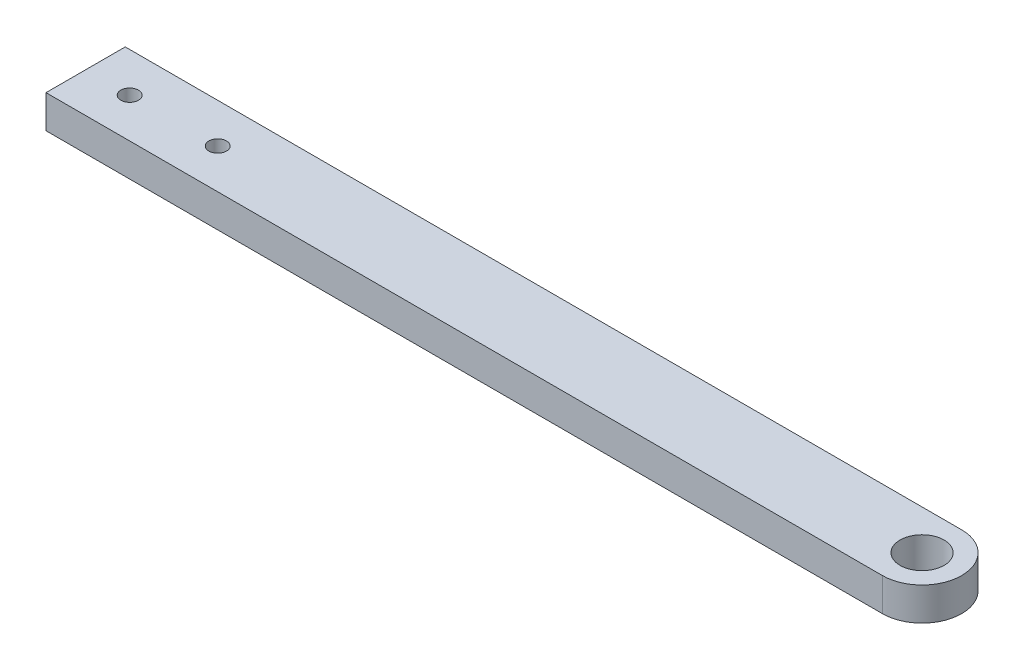
SolidWorks part; units mm, degrees
ref_plane "Front Plane" through (0, 0, 0) normal (0, 0, 1) x (1, 0, 0)
ref_plane "Top Plane" through (0, 0, 0) normal (0, 1, 0) x (1, 0, 0)
ref_plane "Right Plane" through (0, 0, 0) normal (1, 0, 0) x (0, 0, -1)
sketch "Sketch1" plane through (0, 0, 0) normal (0, 1, 0) x (1, 0, 0)
  line L3 (0, 9) -> (-190, 9)
  line L4 (-190, 9) -> (-190, -9)
  line L5 (-190, -9) -> (0, -9)
  arc A1 (0, -9) -> (0, 9) centre (0, 0) ccw
  dimension "D1" = 18
  dimension "D2" = 190
extrude "Boss-Extrude1" add sketch "Sketch1" along normal blind 7.5
sketch "Sketch2" plane through (0, 7.5, 0) normal (0, 1, 0) x (1, 0, 0)
  line L0 (-190, 9) -> (-190, -9) construction
  circle A0 centre (-180, 0) radius 2
  circle A1 centre (-160, 0) radius 2
  dimension "D1" = 4
  dimension "D2" = 20
  dimension "D3" = 10
extrude "Cut-Extrude1" cut sketch "Sketch2" against normal through all
sketch "Sketch3" plane through (0, 7.5, 0) normal (0, 1, 0) x (1, 0, 0)
  circle A0 centre (0, 0) radius 5
  dimension "D1" = 10
extrude "Cut-Extrude2" cut sketch "Sketch3" against normal through all
